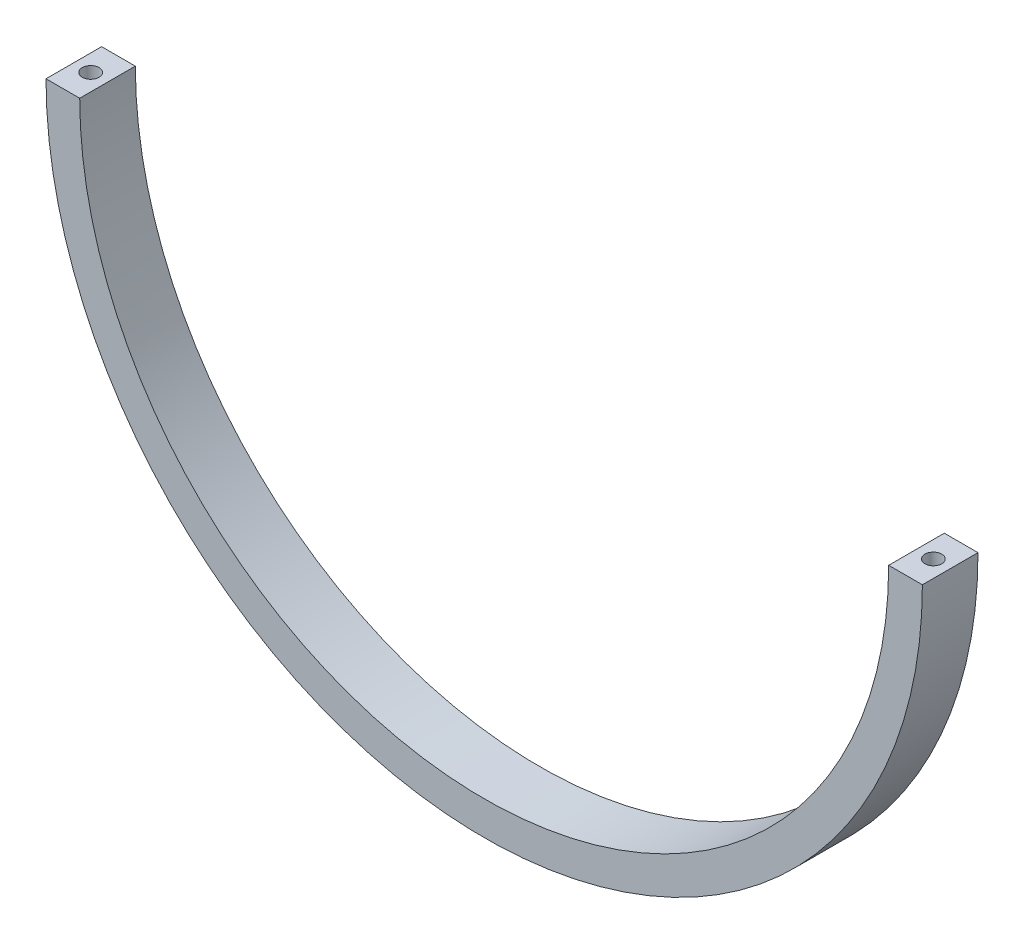
SolidWorks part; units mm, degrees
ref_plane "Front Plane" through (0, 0, 0) normal (0, 0, 1) x (1, 0, 0)
ref_plane "Top Plane" through (0, 0, 0) normal (0, 1, 0) x (1, 0, 0)
ref_plane "Right Plane" through (0, 0, 0) normal (1, 0, 0) x (0, 0, -1)
sketch "Sketch1" plane through (0, 0, 0) normal (0, 0, 1) x (1, 0, 0)
  line L0 (-26, 0) -> (-24, 0)
  line L1 (24, 0) -> (26, 0)
  arc A0 (-26, 0) -> (26, 0) centre (0, 0) ccw
  arc A1 (-24, 0) -> (24, 0) centre (0, 0) ccw
  dimension "D1" = 52
  dimension "D2" = 2
extrude "Boss-Extrude1" add sketch "Sketch1" along normal blind 3.3
sketch "Sketch2" plane through (0, 0, 0) normal (0, 1, 0) x (1, 0, 0)
  line L0 (26, -1.65) -> (-26, -1.65)
  line L1 (-26, 0) -> (-24, 0)
  line L2 (-26, 0) -> (-26, -3.3)
  line L3 (-26, -3.3) -> (-24, -3.3)
  line L4 (-24, 0) -> (-24, -3.3)
  line L5 (24, 0) -> (26, 0)
  line L6 (24, 0) -> (24, -3.3)
  line L7 (24, -3.3) -> (26, -3.3)
  line L8 (26, 0) -> (26, -3.3)
  line L9 (-25, -3.3) -> (-25, 0) construction
  line L10 (25, 0) -> (25, -3.3) construction
  circle A0 centre (25, -1.65) radius 0.5
  circle A1 centre (-25, -1.65) radius 0.5
  dimension "D1" = 1
  dimension "D2" = 1
extrude "Cut-Extrude1" cut sketch "Sketch2" against normal blind 3.3 contours L0 A0 | L0 A0 | L0 A1 | L0 A1
scale "Scale1" scale about centroid uniform scaling yes scale factor 1.9329
scale "Scale2" scale about centroid uniform scaling yes scale factor 1.5
